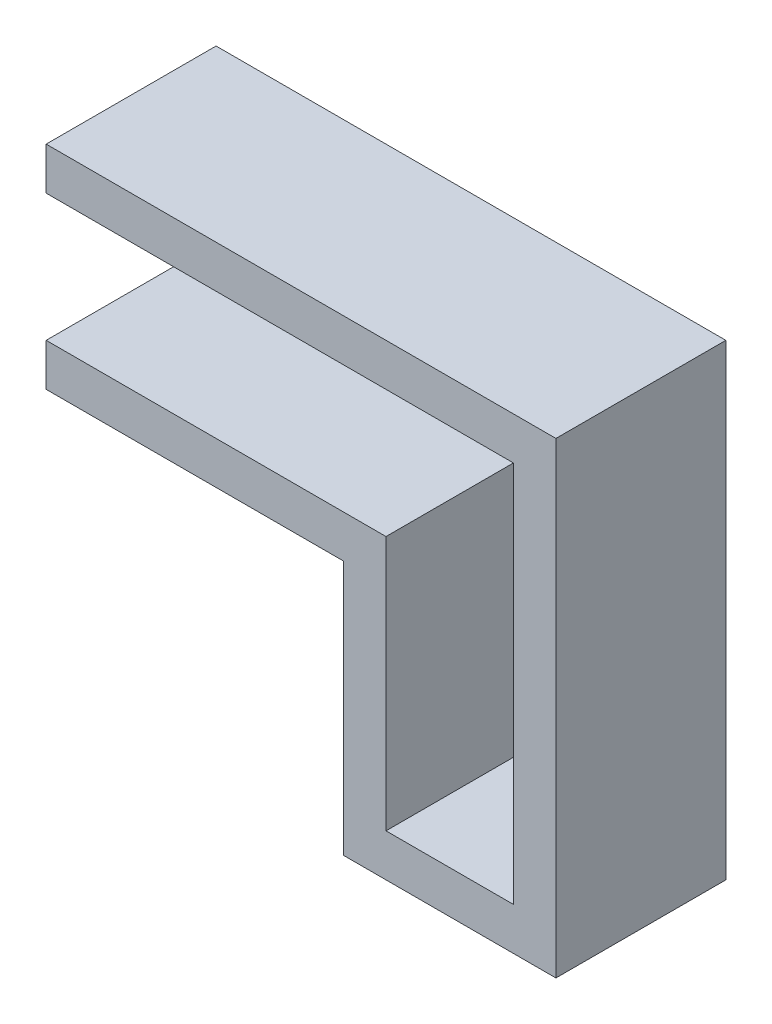
SolidWorks part; units mm, degrees
ref_plane "정면" through (0, 0, 0) normal (0, 0, 1) x (1, 0, 0)
ref_plane "윗면" through (0, 0, 0) normal (0, 1, 0) x (1, 0, 0)
ref_plane "우측면" through (0, 0, 0) normal (1, 0, 0) x (0, 0, -1)
sketch "스케치1" plane through (0, 0, 0) normal (0, 0, 1) x (1, 0, 0)
  line L0 (70, -110) -> (70, -50)
  line L1 (0, 0) -> (120, 0)
  line L2 (0, 0) -> (0, -50)
  line L3 (0, -50) -> (120, -50)
  line L4 (120, 0) -> (120, -50)
  line L5 (0, -50) -> (120, -50)
  line L7 (70, -110) -> (120, -110)
  line L8 (120, -50) -> (120, -110)
  point P7 (68.1704, -50)
  dimension "D1" = 50
  dimension "D2" = 120
  dimension "D3" = 70
  dimension "D4" = 60
extrude "보스-돌출1" add sketch "스케치1" along normal blind 40
sketch "스케치2" plane through (0, 0, 40) normal (0, 0, 1) x (1, 0, 0)
  line L0 (70, -110) -> (120, -110) construction
  line L1 (80, -110) -> (110, -110)
  line L2 (80, -110) -> (80, -40)
  line L3 (80, -40) -> (110, -40)
  line L4 (110, -110) -> (110, -40)
  line L11 (110, -40) -> (110, -10)
  line L12 (120, 0) -> (120, -110) construction
  line L13 (80, -100) -> (110, -100)
  line L14 (110, -10) -> (0, -10)
  line L15 (0, 0) -> (0, -50) construction
  line L16 (0, -10) -> (0, -40)
  line L17 (0, -40) -> (80, -40)
  line L18 (0, 0) -> (120, 0) construction
  line L19 (0, -50) -> (70, -50) construction
  dimension "D1" = 10
  dimension "D2" = 10
  dimension "D3" = 30
  dimension "D4" = 10
  dimension "D5" = 10
extrude "컷-돌출1" cut sketch "스케치2" against normal blind 30
